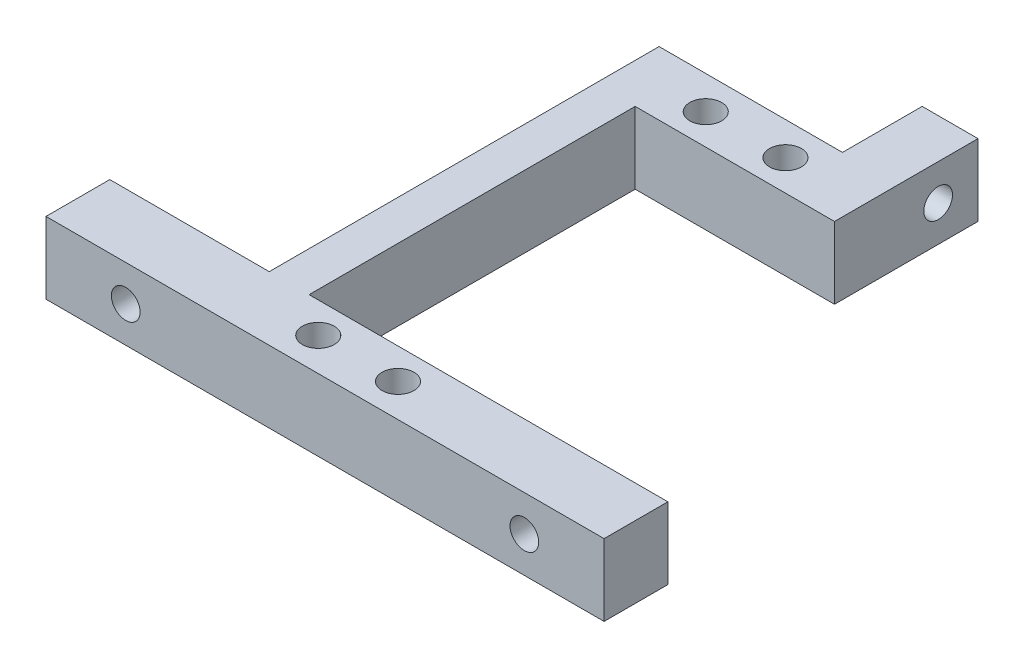
SolidWorks part; units mm, degrees
ref_plane "Plan de face" through (0, 0, 0) normal (0, 0, 1) x (1, 0, 0)
ref_plane "Plan de dessus" through (0, 0, 0) normal (0, 1, 0) x (1, 0, 0)
ref_plane "Plan de droite" through (0, 0, 0) normal (1, 0, 0) x (0, 0, -1)
sketch "Esquisse1" plane through (0, 0, 0) normal (0, 0, 1) x (1, 0, 0)
  line L0 (0, 9) -> (0, 0)
  line L1 (0, 9) -> (70, 9)
  line L2 (0, 0) -> (70, 0)
  line L3 (70, 9) -> (70, 0)
  line L4 (0, 125) -> (0, 0) construction
  circle A0 centre (10, 4.5) radius 1.8
  circle A1 centre (60, 4.5) radius 1.8
  dimension "D3" = 3.6
  dimension "D4" = 3.6
  dimension "D1" = 9
  dimension "D2" = 70
  dimension "D5" = 50
  dimension "D6" = 10
  dimension "D7" = 4.5
  dimension "D8" = 4.5
extrude "Boss.-Extru.1" add sketch "Esquisse1" along normal blind 8
sketch "Esquisse2" plane through (0, 0, 0) normal (0, -1, 0) x (1, 0, 0)
  line L0 (70, 8) -> (70, 0) construction
  line L1 (0, 0) -> (70, 0) construction
  circle A0 centre (30, 3.85) radius 2
  circle A1 centre (40, 3.85) radius 2
  dimension "D1" = 4
  dimension "D2" = 4
  dimension "D3" = 10
  dimension "D4" = 30
  dimension "D5" = 3.85
  dimension "D6" = 3.85
extrude "Enlèv. mat.-Extru.1" cut sketch "Esquisse2" against normal blind 10
sketch "Esquisse3" plane through (0, 9, 0) normal (0, 1, 0) x (1, 0, 0)
  line L10 (55, 0) -> (20, 0)
  line L11 (55, 0) -> (55, 48.9)
  line L12 (20, 0) -> (20, 48.9)
  line L13 (55, 48.9) -> (20, 48.9)
  line L14 (70, 0) -> (0, 0) construction
  line L19 (50, 0) -> (25, 0)
  line L20 (50, 0) -> (50, 40.9)
  line L21 (25, 0) -> (25, 40.9)
  line L22 (50, 40.9) -> (25, 40.9)
  circle A0 centre (30, 44.75) radius 2
  circle A4 centre (40, 44.75) radius 2
  circle A5 centre (40, -3.85) radius 2 construction
  dimension "D3" = 5
  dimension "D4" = 8
  dimension "D7" = 10
  dimension "D8" = 10
  dimension "D5" = 4
  dimension "D6" = 4
  dimension "D9" = 10
  dimension "D1" = 25
  dimension "D2" = 5
  dimension "D10" = 40.9
  dimension "D11" = 3.85
  dimension "D12" = 3.85
extrude "Boss.-Extru.2" add sketch "Esquisse3" against normal blind 9
sketch "Esquisse4" plane through (0, 9, 0) normal (0, 1, 0) x (1, 0, 0)
  line L0 (55, 48.9) -> (50, 48.9)
  line L1 (55, 48.9) -> (55, 0)
  line L2 (50, 48.9) -> (50, 0)
  line L3 (55, 0) -> (50, 0)
  line L4 (55, 48.9) -> (20, 48.9) construction
extrude "Enlèv. mat.-Extru.2" cut sketch "Esquisse4" against normal blind 10
sketch "Esquisse5" plane through (50, 0, 0) normal (1, 0, 0) x (0, 0, -1)
  line L0 (48.9, 9) -> (58.9, 9)
  line L1 (48.9, 9) -> (48.9, 0)
  line L2 (58.9, 9) -> (58.9, 0)
  line L3 (48.9, 0) -> (58.9, 0)
  line L4 (48.9, 0) -> (58.9, 9) construction
  circle A0 centre (53.9, 4.5) radius 1.8
  dimension "D2" = 3.6
  dimension "D1" = 10
extrude "Boss.-Extru.3" add sketch "Esquisse5" against normal blind 7
